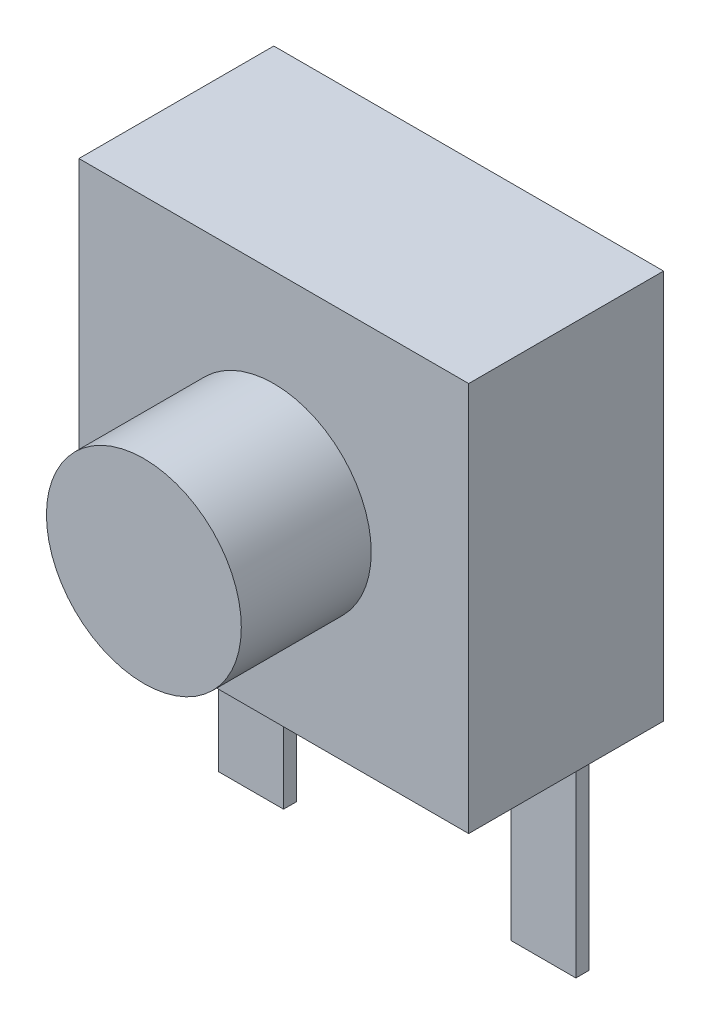
SolidWorks part; units mm, degrees
ref_plane "前视基准面" through (0, 0, 0) normal (0, 0, 1) x (1, 0, 0)
ref_plane "上视基准面" through (0, 0, 0) normal (0, 1, 0) x (1, 0, 0)
ref_plane "右视基准面" through (0, 0, 0) normal (1, 0, 0) x (0, 0, -1)
sketch "草图1" plane through (0, 0, 0) normal (0, 0, 1) x (1, 0, 0)
  line L0 (-1000, 0) -> (49000, 0) construction
  line L1 (0, -1000) -> (0, 49000) construction
  line L2 (-3, 3) -> (3, 3)
  line L3 (3, 3) -> (3, -3)
  line L4 (-3, 3) -> (-3, -3)
  line L5 (-3, -3) -> (3, -3)
  point P10 (0, 3)
  point P11 (3, 0)
  point P12 (-3, 0)
  dimension "D1" = 6
  dimension "D2" = 6
extrude "凸台-拉伸1" add sketch "草图1" along normal blind 3
sketch "草图2" plane through (0, 0, 3) normal (0, 0, 1) x (1, 0, 0)
  circle A0 centre (0, 0) radius 1.5
extrude "凸台-拉伸2" add sketch "草图2" along normal blind 2
sketch "草图4" plane through (0, -3, 0) normal (0, -1, 0) x (1, 0, 0)
  line L0 (0, -1000) -> (0, 49000) construction
  line L1 (2.25, 2.1495) -> (2.25, -0.7714) construction
  line L2 (-2.25, 2.1495) -> (-2.25, -0.7714) construction
  line L3 (-3.6318, 1) -> (3.4524, 1) construction
  line L4 (-3, 0) -> (3, 0) construction
  line L5 (1.75, 1.1) -> (2.75, 1.1)
  line L6 (2.75, 1.1) -> (2.75, 0.9)
  line L7 (1.75, 1.1) -> (1.75, 0.9)
  line L8 (1.75, 0.9) -> (2.75, 0.9)
  point P16 (2.25, 1.1)
  point P17 (2.75, 1)
  point P18 (1.75, 1)
  dimension "D1" = 4.5
  dimension "D2" = 1
  dimension "D3" = 0.2
  dimension "D4" = 1
ref_plane "基准面1" through (2.25, 0, 0) normal (1, 0, 0) x (0, 0, -1)
sketch "草图6" plane through (2.25, 0, 0) normal (1, 0, 0) x (0, 0, -1)
  line L0 (-1000, 0) -> (49000, 0) construction
  line L2 (-4.4082, 3.25) -> (1.7946, 3.25) construction
  line L3 (-1.1, -3) -> (-1.1, -6)
  dimension "D1" = 3
sweep "扫描3" add profiles "草图4" path "草图6"
mirror "镜向1" about plane through (0, 0, 0) normal (1, 0, 0) of "扫描3"
